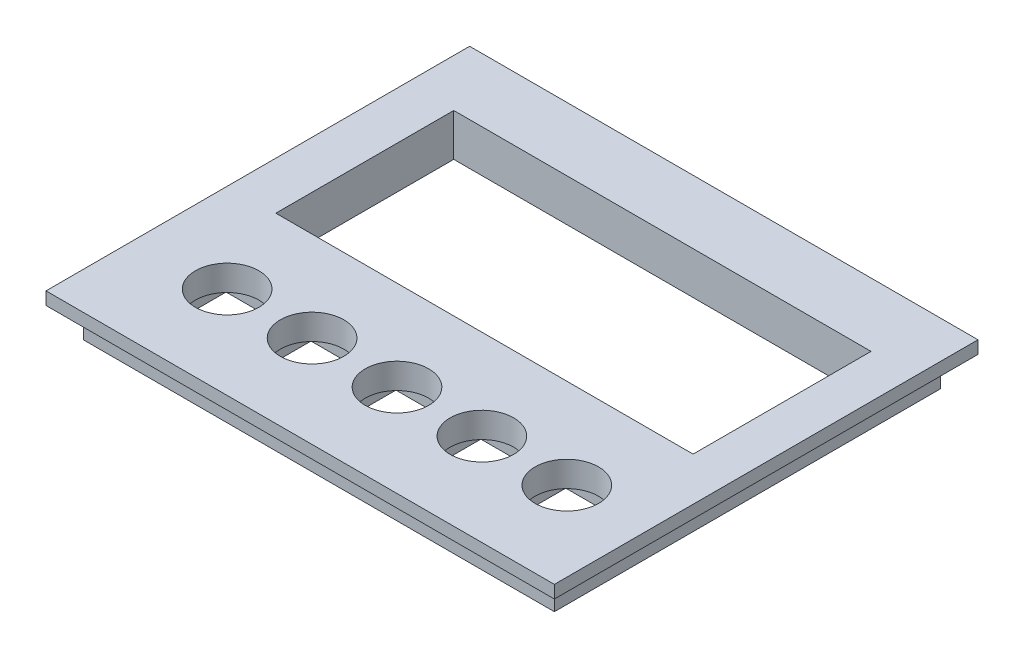
SolidWorks part; units mm, degrees
ref_plane "Front Plane" through (0, 0, 0) normal (0, 0, 1) x (1, 0, 0)
ref_plane "Top Plane" through (0, 0, 0) normal (0, 1, 0) x (1, 0, 0)
ref_plane "Right Plane" through (0, 0, 0) normal (1, 0, 0) x (0, 0, -1)
sketch "Sketch1" plane through (0, 0, 0) normal (0, 1, 0) x (1, 0, 0)
  line L1 (-59.6887, 52.0519) -> (60.3113, 52.0519)
  line L2 (-59.6887, 52.0519) -> (-59.6887, -47.9481)
  line L3 (-59.6887, -47.9481) -> (60.3113, -47.9481)
  line L4 (60.3113, 52.0519) -> (60.3113, -47.9481)
  dimension "D1" = 100
  dimension "D2" = 120
extrude "Boss-Extrude1" add sketch "Sketch1" along normal blind 10
sketch "Sketch2" plane through (0, 10, 0) normal (0, 1, 0) x (1, 0, 0)
  line L0 (60.3113, 52.0519) -> (-59.6887, 52.0519) construction
  line L1 (-48.4387, 37.0519) -> (50.0613, 37.0519)
  line L2 (-48.4387, 37.0519) -> (-48.4387, -4.9481)
  line L3 (-48.4387, -4.9481) -> (50.0613, -4.9481)
  line L4 (50.0613, 37.0519) -> (50.0613, -4.9481)
  line L5 (-59.6887, 52.0519) -> (-59.6887, -47.9481) construction
  dimension "D1" = 98.5
  dimension "D2" = 42
  dimension "D3" = 15
  dimension "D4" = 11.25
extrude "Cut-Extrude1" cut sketch "Sketch2" against normal blind 10
sketch "Sketch3" plane through (0, 0, 0) normal (0, -1, 0) x (1, 0, 0)
  line L0 (-59.6887, 47.9481) -> (60.3113, 47.9481) construction
  line L1 (-55.2887, 43.5481) -> (55.9113, 43.5481)
  line L2 (-55.2887, 43.5481) -> (-55.2887, -47.6519)
  line L3 (-55.2887, -47.6519) -> (55.9113, -47.6519)
  line L4 (55.9113, 43.5481) -> (55.9113, -47.6519)
  line L5 (-59.6887, -52.0519) -> (-59.6887, 47.9481) construction
  line L7 (60.3113, -52.0519) -> (-59.6887, -52.0519)
  line L8 (60.3113, -52.0519) -> (60.3113, 47.9481)
  line L9 (60.3113, 47.9481) -> (-59.6887, 47.9481)
  line L10 (-59.6887, -52.0519) -> (-59.6887, 47.9481)
  dimension "D1" = 4.4
  dimension "D2" = 4.4
  dimension "D3" = 4.4
  dimension "D4" = 4.4
extrude "Cut-Extrude3" cut sketch "Sketch3" against normal blind 7
sketch "Sketch4" plane through (0, 0, 0) normal (0, -1, 0) x (1, 0, 0)
  line L0 (-48.4387, 4.9481) -> (50.0613, 4.9481) construction
  line L1 (-48.1793, 41.9481) -> (-30.1793, 41.9481)
  line L2 (-48.1793, 41.9481) -> (-48.1793, 16.9481)
  line L3 (-48.1793, 16.9481) -> (-30.1793, 16.9481)
  line L4 (-30.1793, 41.9481) -> (-30.1793, 16.9481)
  line L5 (-28.1338, 41.9481) -> (-10.1338, 41.9481)
  line L6 (-28.1338, 41.9481) -> (-28.1338, 16.9481)
  line L7 (-28.1338, 16.9481) -> (-10.1338, 16.9481)
  line L8 (-10.1338, 41.9481) -> (-10.1338, 16.9481)
  line L9 (-8.0883, 41.9481) -> (9.9117, 41.9481)
  line L10 (-8.0883, 41.9481) -> (-8.0883, 16.9481)
  line L11 (-8.0883, 16.9481) -> (9.9117, 16.9481)
  line L12 (9.9117, 41.9481) -> (9.9117, 16.9481)
  line L13 (11.9573, 41.9481) -> (29.9573, 41.9481)
  line L14 (11.9573, 41.9481) -> (11.9573, 16.9481)
  line L15 (11.9573, 16.9481) -> (29.9573, 16.9481)
  line L16 (29.9573, 41.9481) -> (29.9573, 16.9481)
  line L17 (32.0028, 41.9481) -> (50.0028, 41.9481)
  line L18 (32.0028, 41.9481) -> (32.0028, 16.9481)
  line L19 (32.0028, 16.9481) -> (50.0028, 16.9481)
  line L20 (50.0028, 41.9481) -> (50.0028, 16.9481)
  line L21 (-48.1793, -19.4827) -> (-48.1793, 51.1477) construction
  line L23 (50.0028, -6.721) -> (50.0028, 58.8046) construction
  dimension "D1" = 18
  dimension "D2" = 25
  dimension "D3" = 12
  dimension "D5" = 0
  dimension "D6" = 0
  dimension "D4" = 5
extrude "Cut-Extrude4" cut sketch "Sketch4" against normal blind 4
sketch "Sketch5" plane through (0, 4, 0) normal (0, -1, 0) x (1, 0, 0)
  line L0 (50.0028, 41.9481) -> (32.0028, 41.9481) construction
  line L1 (32.0028, 16.9481) -> (33.0028, 16.9481)
  line L2 (32.0028, 16.9481) -> (32.0028, 41.9481)
  line L3 (32.0028, 41.9481) -> (33.0028, 41.9481)
  line L4 (33.0028, 16.9481) -> (33.0028, 41.9481)
  line L5 (11.9573, 16.9481) -> (12.9573, 16.9481)
  line L6 (11.9573, 16.9481) -> (11.9573, 41.9481)
  line L7 (11.9573, 41.9481) -> (12.9573, 41.9481)
  line L8 (12.9573, 16.9481) -> (12.9573, 41.9481)
  line L9 (-8.0883, 16.9481) -> (-7.0883, 16.9481)
  line L10 (-8.0883, 16.9481) -> (-8.0883, 41.9481)
  line L11 (-8.0883, 41.9481) -> (-7.0883, 41.9481)
  line L12 (-7.0883, 16.9481) -> (-7.0883, 41.9481)
  line L13 (-28.1338, 16.9481) -> (-27.1338, 16.9481)
  line L14 (-28.1338, 16.9481) -> (-28.1338, 41.9481)
  line L15 (-28.1338, 41.9481) -> (-27.1338, 41.9481)
  line L16 (-27.1338, 16.9481) -> (-27.1338, 41.9481)
  line L17 (-48.1793, 16.9481) -> (-47.1793, 16.9481)
  line L18 (-48.1793, 16.9481) -> (-48.1793, 41.9481)
  line L19 (-48.1793, 41.9481) -> (-47.1793, 41.9481)
  line L20 (-47.1793, 16.9481) -> (-47.1793, 41.9481)
  line L21 (-48.1793, 41.9481) -> (-48.1793, 16.9481) construction
  dimension "D1" = 1
  dimension "D3" = 0
  dimension "D2" = 5
extrude "Cut-Extrude6" cut sketch "Sketch5" against normal blind 2.5
sketch "Sketch6" plane through (0, 4, 0) normal (0, -1, 0) x (1, 0, 0)
  line L0 (33.0028, 16.9481) -> (50.0028, 16.9481) construction
  line L1 (50.0028, 16.9481) -> (50.0028, 41.9481) construction
  line L2 (-30.1793, 16.9481) -> (-30.1793, 41.9481) construction
  circle A0 centre (41.5028, 26.1981) radius 7.49
  circle A1 centre (21.4573, 26.1981) radius 7.49
  circle A2 centre (1.4117, 26.1981) radius 7.49
  circle A3 centre (-18.6338, 26.1981) radius 7.49
  circle A4 centre (-38.6793, 26.1981) radius 7.49
  dimension "D1" = 9.25
  dimension "D2" = 8.5
  dimension "D4" = 8.5
  dimension "D3" = 5
extrude "Cut-Extrude12" cut sketch "Sketch6" against normal through all
